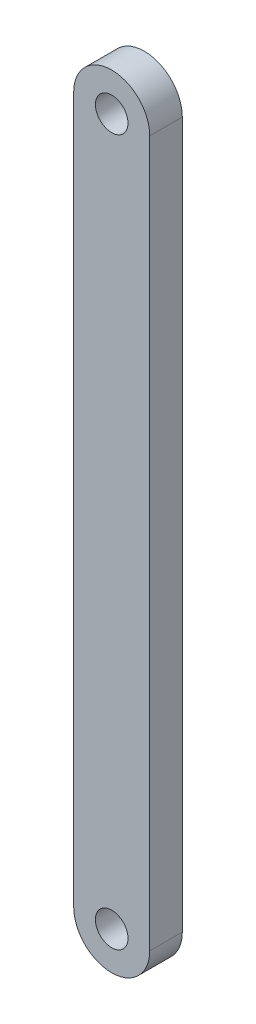
SolidWorks part; units mm, degrees
material "ABS"
ref_plane "Front Plane" through (0, 0, 0) normal (0, 0, 1) x (1, 0, 0)
ref_plane "Top Plane" through (0, 0, 0) normal (0, 1, 0) x (1, 0, 0)
ref_plane "Right Plane" through (0, 0, 0) normal (1, 0, 0) x (0, 0, -1)
sketch "Sketch1" plane through (0, 0, 0) normal (0, 0, 1) x (1, 0, 0)
  line L0 (0, 32.5) -> (0, -32.5) construction
  line L1 (3.5, 32.5) -> (3.5, -32.5)
  line L2 (-3.5, 32.5) -> (-3.5, -32.5)
  arc A0 (3.5, 32.5) -> (-3.5, 32.5) centre (0, 32.5) ccw
  arc A1 (-3.5, -32.5) -> (3.5, -32.5) centre (0, -32.5) ccw
  circle A2 centre (0, -32.5) radius 1.5
  circle A3 centre (0, 32.5) radius 1.5
  point P3 (0, 0)
  dimension "D3" = 3
  dimension "D1" = 65
  dimension "D2" = 7
extrude "Boss-Extrude1" add sketch "Sketch1" along normal mid plane 3
